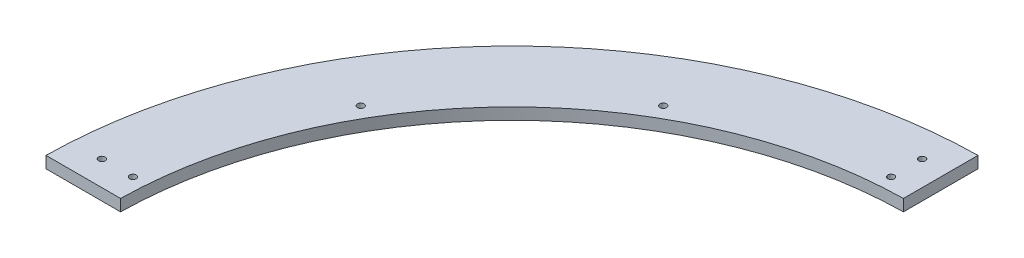
SolidWorks part; units mm, degrees
material "Pine"
ref_plane "Front Plane" through (0, 0, 0) normal (0, 0, 1) x (1, 0, 0)
ref_plane "Top Plane" through (0, 0, 0) normal (0, 1, 0) x (1, 0, 0)
ref_plane "Right Plane" through (0, 0, 0) normal (1, 0, 0) x (0, 0, -1)
sketch "Sketch1" plane through (0, 0, 0) normal (0, 1, 0) x (1, 0, 0)
  line L0 (-406.4, 0) -> (-482.6, 0)
  line L1 (406.4, 0) -> (482.6, 0)
  arc A0 (-406.4, 0) -> (406.4, 0) centre (0, 0) cw
  arc A1 (-482.6, 0) -> (482.6, 0) centre (0, 0) cw
  dimension "D2" = 406.4
  dimension "D1" = 76.2
extrude "Boss-Extrude1" add sketch "Sketch1" along normal blind 11.9062
sketch "Sketch2" plane through (0, 11.9062, 0) normal (0, 1, 0) x (1, 0, 0)
  line L1 (-6.35, 406.3504) -> (6.35, 406.3504)
  line L2 (-6.35, 406.3504) -> (-6.35, 444.5)
  line L3 (-6.35, 444.5) -> (6.35, 444.5)
  line L4 (6.35, 406.3504) -> (6.35, 444.5)
  line L8 (406.3504, 6.35) -> (444.5, 6.35)
  line L9 (0, 0) -> (0, 406.3504) construction
  line L14 (0, 482.6) -> (0, 406.4) construction
  line L15 (406.3504, 6.35) -> (406.3504, -6.35)
  line L16 (406.3504, -6.35) -> (444.5, -6.35)
  line L17 (444.5, 6.35) -> (444.5, -6.35)
  line L18 (6.35, -406.3504) -> (6.35, -444.5)
  line L19 (6.35, -406.3504) -> (-6.35, -406.3504)
  line L20 (-6.35, -406.3504) -> (-6.35, -444.5)
  line L21 (6.35, -444.5) -> (-6.35, -444.5)
  line L22 (-406.3504, -6.35) -> (-444.5, -6.35)
  line L23 (-406.3504, -6.35) -> (-406.3504, 6.35)
  line L24 (-406.3504, 6.35) -> (-444.5, 6.35)
  line L25 (-444.5, -6.35) -> (-444.5, 6.35)
  arc A0 (406.4, 0) -> (-406.4, 0) centre (0, 0) ccw construction
  arc A1 (482.6, 0) -> (-482.6, 0) centre (0, 0) ccw construction
  point P7 (0, 406.3504)
  point P16 (0, 0)
  point P23 (0, 444.5)
  point P33 (0, 0)
  dimension "D1" = 38.1
  dimension "D2" = 12.7
  dimension "D3" = 4
extrude "Cut-Extrude1" cut sketch "Sketch2" against normal through all
hole_wizard "1/4 Clearance Hole1" positions "Sketch6" profile "Sketch7" hole size "1/4" standard "ANSI Inch" end condition through all
sketch "Sketch6" plane through (0, 11.9062, 0) normal (0, 1, 0) x (1, 0, 0)
  line L0 (0, 444.5) -> (0, 406.4) construction
  line L1 (6.35, 444.5) -> (-6.35, 444.5) construction
  line L2 (0, 406.4) -> (-31.75, 406.4) construction
  line L3 (-31.75, 406.4) -> (-31.75, 419.1) construction
  line L4 (-31.75, 419.1) -> (-31.75, 450.85) construction
  line L6 (-444.5, 0) -> (-406.4, 0) construction
  line L7 (-406.4, 0) -> (-406.4, 31.75) construction
  line L8 (-406.4, 31.75) -> (-419.1, 31.75) construction
  line L9 (-419.1, 31.75) -> (-450.85, 31.75) construction
  line L10 (-6.35, 444.5) -> (-6.35, 406.3504) construction
  line L11 (-406.4, 0) -> (-351.9527, 203.2) construction
  line L12 (-351.9527, 203.2) -> (-203.2, 351.9527) construction
  line L13 (-203.2, 351.9527) -> (0, 406.4) construction
  line L15 (-351.9527, 203.2) -> (-365.7009, 211.1375) construction
  line L16 (-203.2, 351.9527) -> (-211.1375, 365.7009) construction
  line L17 (0, 0) -> (-287.3682, 287.3682) construction
  arc A0 (-6.35, 406.3504) -> (-406.3504, 6.35) centre (0, 0) ccw construction
  point P8 (-31.75, 419.1)
  point P10 (-31.75, 450.85)
  point P21 (-419.1, 31.75)
  point P22 (-450.85, 31.75)
  point P52 (-211.1375, 365.7009)
  point P54 (-365.7009, 211.1375)
  dimension "D1" = 38.1
  dimension "D2" = 25.4
  dimension "D3" = 12.7
  dimension "D4" = 31.75
  dimension "D5" = 15.875
sketch "Sketch7" plane through (-365.7009, 11.9062, -211.1375) normal (1, 0, 0) x (0, 0, 1)
  line L0 (0, 0) -> (0, 11.9062)
  line L1 (0, 11.9062) -> (3.3782, 11.9062)
  line L2 (3.3782, 11.9062) -> (3.3782, 0)
  line L5 (3.3782, 0) -> (0, 0)
  line L11 (0, -6.35) -> (0, 107.95) construction
  dimension "Thru Hole Dia." = 6.7564
  dimension "Thru Hole Depth" = 11.9062
sketch "Sketch8" plane through (0, 11.9062, 0) normal (0, 1, 0) x (1, 0, 0)
  line L1 (0, 482.6) -> (482.6, 482.6)
  line L2 (0, 482.6) -> (0, 0)
  line L3 (0, 0) -> (482.6, 0)
  line L4 (482.6, 482.6) -> (482.6, 0)
  arc A0 (482.6, 0) -> (-482.6, 0) centre (0, 0) ccw construction
extrude "Cut-Extrude4" cut sketch "Sketch8" against normal through all
sketch "Sketch12" plane through (0, 11.9062, 0) normal (0, 1, 0) x (1, 0, 0)
  line L1 (-6.35, 406.3504) -> (0, 406.3504)
  line L2 (-6.35, 406.3504) -> (-6.35, 482.6)
  line L3 (-6.35, 482.6) -> (0, 482.6)
  line L4 (0, 406.3504) -> (0, 482.6)
  line L5 (-406.3504, 6.35) -> (-482.6, 6.35)
  line L6 (-406.3504, 6.35) -> (-406.3504, 0)
  line L7 (-406.3504, 0) -> (-482.6, 0)
  line L8 (-482.6, 6.35) -> (-482.6, 0)
extrude "Cut-Extrude6" cut sketch "Sketch12" against normal through all
ref_plane "Plane1" through (0, 0, 0) normal (0.7071, 0, -0.7071) x (-0.7071, 0, -0.7071)
ref_plane "Plane2" through (-206.3502, 0, -206.3502) normal (-0.7071, 0, -0.7071) x (-0.7071, 0, 0.7071)
ref_plane "Plane3" through (-341.2497, 0, -341.2497) normal (-0.7071, 0, -0.7071) x (-0.7071, 0, 0.7071)
